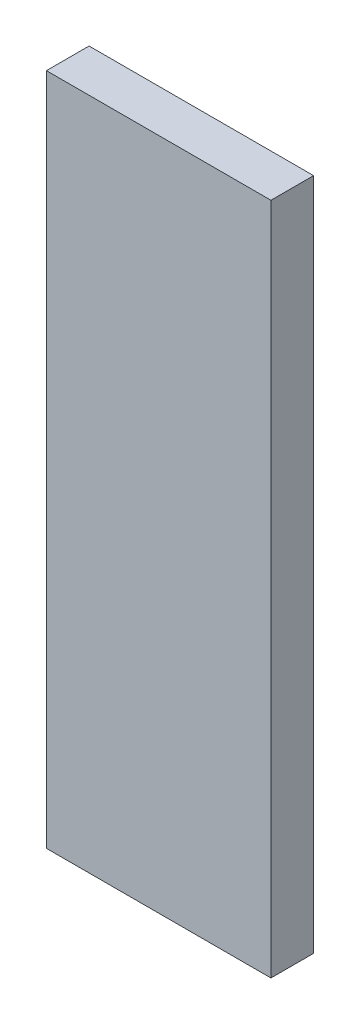
SolidWorks part; units mm, degrees
ref_plane "Front Plane" through (0, 0, 0) normal (0, 0, 1) x (1, 0, 0)
ref_plane "Top Plane" through (0, 0, 0) normal (0, 1, 0) x (1, 0, 0)
ref_plane "Right Plane" through (0, 0, 0) normal (1, 0, 0) x (0, 0, -1)
sketch "Sketch1" plane through (0, 0, 0) normal (0, 0, 1) x (1, 0, 0)
  line L1 (0, 0) -> (100, 0)
  line L2 (0, 0) -> (0, 300)
  line L3 (0, 300) -> (100, 300)
  line L4 (100, 0) -> (100, 300)
  dimension "D1" = 100
  dimension "D2" = 300
extrude "Boss-Extrude1" add sketch "Sketch1" along normal blind 19
